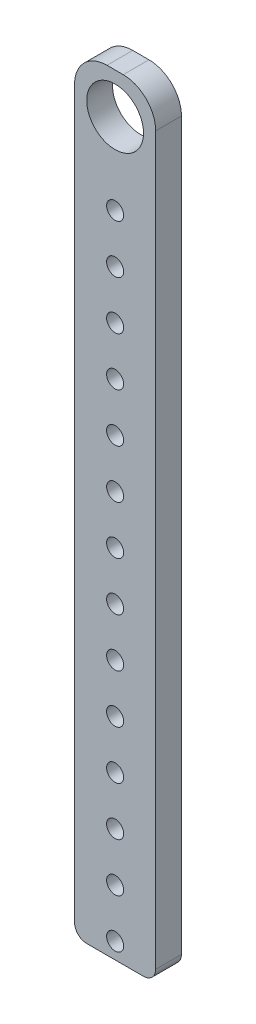
SolidWorks part; units mm, degrees
ref_plane "Front Plane" through (0, 0, 0) normal (0, 0, 1) x (1, 0, 0)
ref_plane "Top Plane" through (0, 0, 0) normal (0, 1, 0) x (1, 0, 0)
ref_plane "Right Plane" through (0, 0, 0) normal (1, 0, 0) x (0, 0, -1)
sketch "Sketch1" plane through (0, 0, 0) normal (0, 0, 1) x (1, 0, 0)
  line L0 (0, 95) -> (0, -95) construction
  line L1 (-10, -95) -> (10, -95)
  line L2 (-10, -95) -> (-10, 95)
  line L3 (-10, 95) -> (10, 95)
  line L4 (10, -95) -> (10, 95)
  line L5 (-10, -95) -> (10, 95) construction
  line L6 (-10, 95) -> (10, -95) construction
  circle A26 centre (0, -91) radius 2.1
  circle A27 centre (0, -79) radius 2.1
  circle A28 centre (0, -67) radius 2.1
  circle A29 centre (0, -55) radius 2.1
  circle A30 centre (0, -43) radius 2.1
  circle A31 centre (0, -31) radius 2.1
  circle A32 centre (0, -19) radius 2.1
  circle A33 centre (0, 85) radius 7
  circle A34 centre (0, -7) radius 2.1
  circle A35 centre (0, 5) radius 2.1
  circle A36 centre (0, 17) radius 2.1
  circle A37 centre (0, 29) radius 2.1
  circle A38 centre (0, 41) radius 2.1
  circle A39 centre (0, 53) radius 2.1
  circle A40 centre (0, 65) radius 2.1
  point P0 (0, 0)
  dimension "D3" = 14
  dimension "D8" = 4.2
  dimension "D1" = 190
  dimension "D2" = 20
  dimension "D4" = 10
  dimension "D9" = 4
  dimension "D10" = 14
extrude "Boss-Extrude1" add sketch "Sketch1" along normal blind 6.35
fillet "Fillet1" radius 3 2 edges at (10, -95, 3.175) (-10, -95, 3.175)
fillet "Fillet2" radius 8 2 edges at (10, 95, 3.175) (-10, 95, 3.175)
